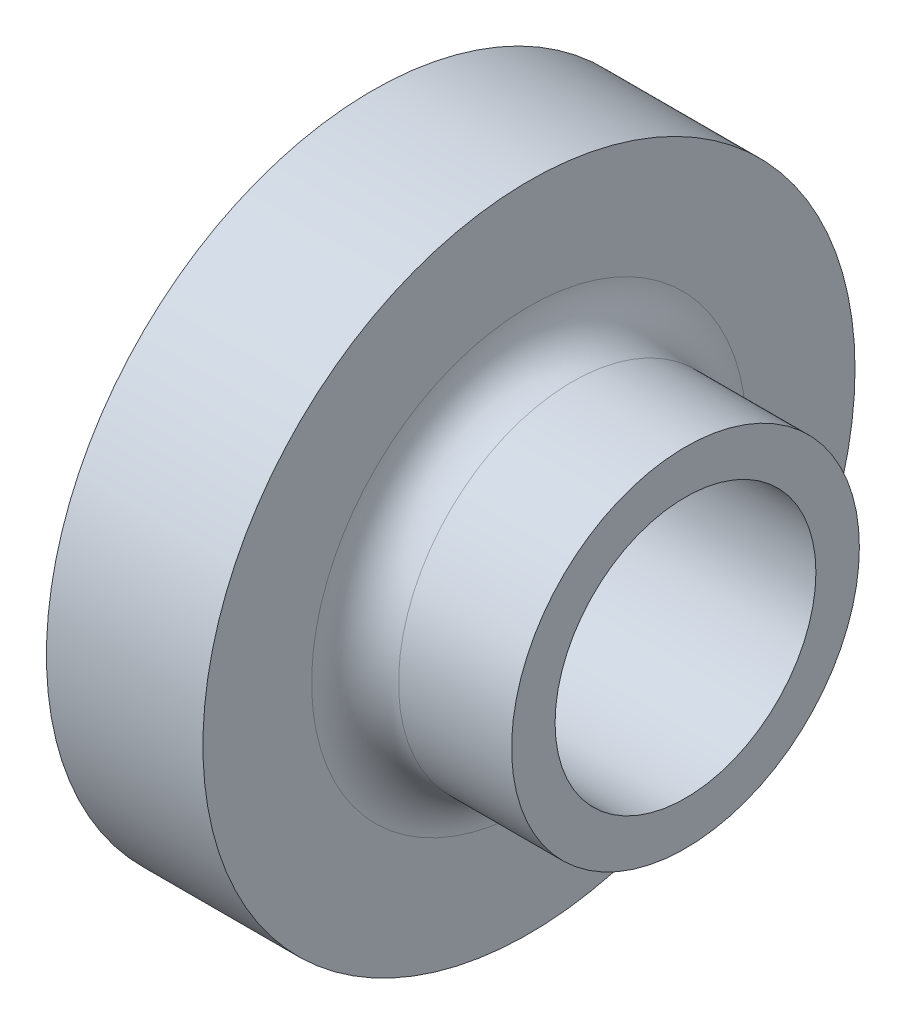
SolidWorks part; units mm, degrees
ref_plane "Ön Düzlem" through (0, 0, 0) normal (0, 0, 1) x (1, 0, 0)
ref_plane "Üst Düzlem" through (0, 0, 0) normal (0, 1, 0) x (1, 0, 0)
ref_plane "Sağ Düzlem" through (0, 0, 0) normal (1, 0, 0) x (0, 0, -1)
sketch "Sketch2" plane through (0, 0, 0) normal (0, 0, 1) x (1, 0, 0)
  line L0 (13.9591, 37.5) -> (31.9591, 37.5)
  line L1 (31.9591, 37.5) -> (31.9591, 20)
  line L2 (31.9591, 20) -> (49.9591, 20)
  line L3 (49.9591, 20) -> (49.9591, 15)
  line L4 (49.9591, 15) -> (13.9591, 15)
  line L5 (13.9591, 15) -> (13.9591, 37.5)
  line L6 (66.8659, 0) -> (0, 0) construction
  dimension "D1" = 15
  dimension "D2" = 36
  dimension "D3" = 5
  dimension "D4" = 18
  dimension "D5" = 37.5
revolve "Revolve1" add sketch "Sketch2" angle 360 about L6
fillet "Fillet1" radius 5 1 edges at (31.9591, 0, -20)
